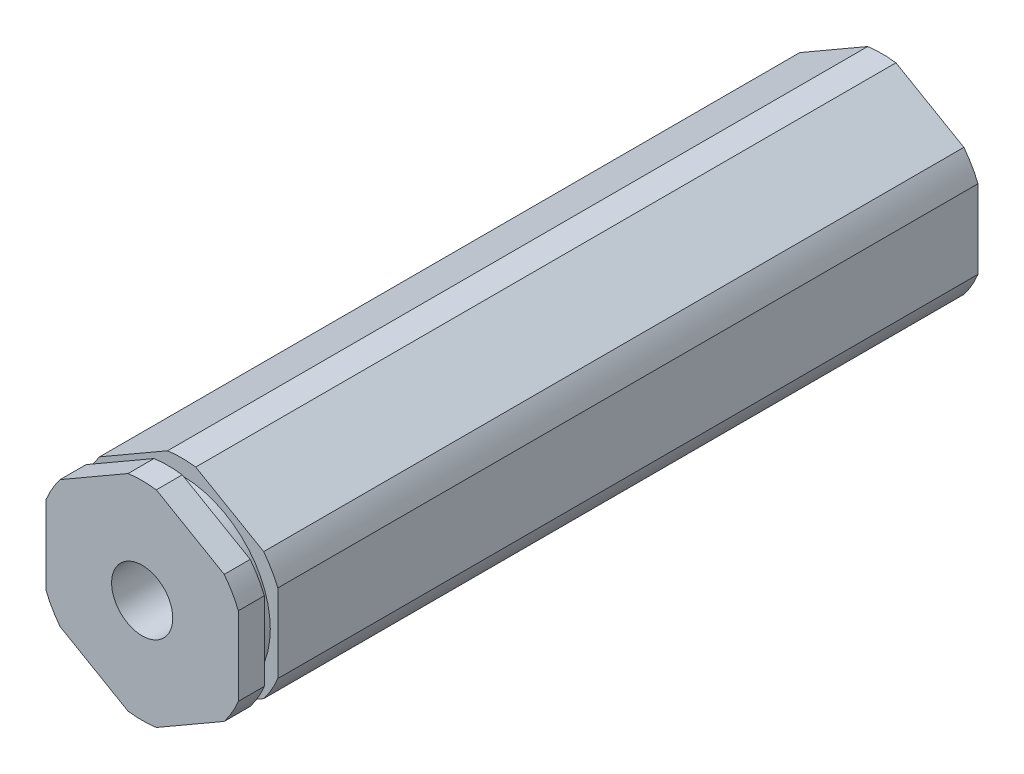
SolidWorks part; units mm, degrees
ref_plane "Front Plane" through (0, 0, 0) normal (0, 0, 1) x (1, 0, 0)
ref_plane "Top Plane" through (0, 0, 0) normal (0, 1, 0) x (1, 0, 0)
ref_plane "Right Plane" through (0, 0, 0) normal (1, 0, 0) x (0, 0, -1)
sketch "Sketch1" plane through (0, 0, 0) normal (0, 0, 1) x (1, 0, 0)
  line L1 (0, 7.3323) -> (-6.35, 3.6662)
  line L2 (-6.35, 3.6662) -> (-6.35, -3.6662)
  line L3 (-6.35, -3.6662) -> (0, -7.3323)
  line L4 (0, -7.3323) -> (6.35, -3.6662)
  line L5 (6.35, -3.6662) -> (6.35, 3.6662)
  line L6 (6.35, 3.6662) -> (0, 7.3323)
  circle A0 centre (0, 0) radius 6.35 construction
  circle A1 centre (0, 0) radius 6.858
  dimension "D1" = 12.7
  dimension "D2" = 13.716
extrude "Boss-Extrude1" add sketch "Sketch1" along normal mid plane 48.8315 contours L5 A1 L6 L1 L2 L3 L4
sketch "Sketch6" plane through (0, 0, 0) normal (0, 0, 1) x (1, 0, 0)
  line L0 (5.4183, 4.2041) -> (0.9317, 6.7944) construction
  circle A0 centre (0, 0) radius 6.35
hole_wizard "#10-32 Tapped Hole1" positions "3DSketch1" profile "Sketch2" tap size "#10-32" standard "ANSI Inch"
sketch3d "3DSketch1"
  line L0 (0, 0, 24.4157) -> (0, 0, -24.4157) construction
  line L1 (0, 0, 24.4157) -> (0, 0, -24.4157) construction
  point P0 (0, 0, 24.4157)
  point P4 (0, 0, -24.4157)
sketch "Sketch2" plane through (0, 0, 24.4157) normal (1, 0, 0) x (0, -1, 0)
  line L0 (0, 0) -> (0, 17.5608)
  line L1 (0, 17.5608) -> (2.0193, 16.3474)
  line L2 (2.0193, 16.3474) -> (2.0193, 0)
  line L5 (2.0193, 0) -> (0, 0)
  line L10 (0, 17.5608) -> (-2.0193, 16.3474) construction
  line L11 (0, -6.35) -> (0, 107.95) construction
  dimension "Tap Drill Dia." = 4.0386
  dimension "Tap Drill Depth" = 16.3474
  dimension "Drill Angle" = 118
cosmetic thread "Hole Thread1" parameters "D1"=13.97, "D2"=4.826
cosmetic thread "Hole Thread2" parameters "D1"=13.97, "D2"=4.826
sketch "Sketch5" plane through (0, 0, 0) normal (1, 0, 0) x (0, 0, -1)
  line L0 (24.4157, 6.858) -> (-24.4157, 6.858) construction
  line L1 (-22.7012, 6.858) -> (-21.8122, 6.858)
  line L2 (-22.7012, 6.858) -> (-22.7012, 5.8547)
  line L3 (-22.7012, 5.8547) -> (-21.8122, 5.8547)
  line L4 (-21.8122, 6.858) -> (-21.8122, 5.8547)
  line L5 (-165.0472, 0) -> (-158.8423, 0) construction
  dimension "D1" = 5.8547
  dimension "D2" = 0.889
  dimension "D3" = 1.7145
revolve "Cut-Revolve1" cut sketch "Sketch5" angle 360 about L5
